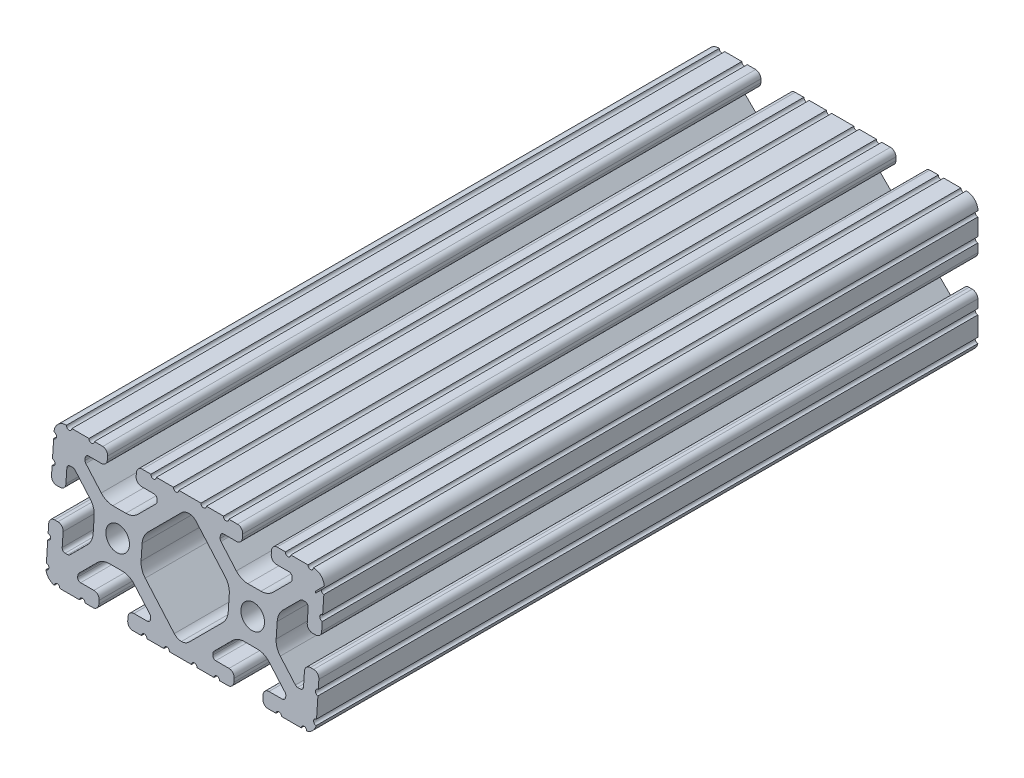
SolidWorks part; units mm, degrees
material "6005A-T61"
ref_plane "Front Plane" through (0, 0, 0) normal (0, 0, 1) x (1, 0, 0)
ref_plane "Top Plane" through (0, 0, 0) normal (0, 1, 0) x (1, 0, 0)
ref_plane "Right Plane" through (0, 0, 0) normal (1, 0, 0) x (0, 0, -1)
sketch "Sketch1" plane through (0, 0, 0) normal (0, 0, 1) x (1, 0, 0)
  line L0 (-3.1211, -19.05) -> (3.1211, -19.05)
  line L1 (-38.1, 10.287) -> (-38.1, 14.3752)
  line L2 (0, -34.5561) -> (0, 32.8014) construction
  line L3 (-38.1, 0) -> (0, 0) construction
  line L4 (-38.1, 9.5497) -> (-38.1, 10.287)
  line L5 (-19.05, 19.05) -> (-19.05, -20.2827) construction
  line L6 (0, -15.1247) -> (0, -15.1131) construction
  line L7 (9.1761, 12.9058) -> (13.8525, 8.2294)
  line L8 (8.9158, 14.097) -> (8.9158, 13.5344)
  line L9 (13.4112, 14.986) -> (9.8048, 14.986)
  line L10 (14.986, 17.4968) -> (14.986, 16.5608)
  line L11 (10.9975, 19.05) -> (13.4328, 19.05)
  line L12 (8.6331, 19.05) -> (9.4735, 19.05)
  line L13 (4.6451, 19.05) -> (8.6331, 19.05)
  line L14 (31.792, 10.0266) -> (27.1976, 5.4321)
  line L15 (33.147, 10.287) -> (32.4207, 10.287)
  line L16 (29.2071, 19.05) -> (33.2963, 19.05)
  line L17 (28.4698, 19.05) -> (29.2071, 19.05)
  line L18 (-38.1, 5.6388) -> (-38.1, 8.0257)
  line L19 (24.5589, 19.05) -> (26.9458, 19.05)
  line L20 (23.114, 16.5608) -> (23.114, 17.4806)
  line L21 (28.2952, 14.986) -> (24.6888, 14.986)
  line L22 (29.1842, 13.5344) -> (29.1842, 14.097)
  line L23 (-34.036, 9.398) -> (-34.036, 5.6388)
  line L24 (-35.6108, 4.064) -> (-36.5252, 4.064)
  line L25 (24.2475, 8.2294) -> (28.9239, 12.9058)
  line L26 (25.8064, -2.0735) -> (25.8064, 2.0735)
  line L27 (35.6108, 4.064) -> (36.5252, 4.064)
  line L28 (34.036, 9.398) -> (34.036, 5.6388)
  line L29 (38.1, 5.6388) -> (38.1, 8.0257)
  line L30 (38.1, 9.5497) -> (38.1, 10.287)
  line L31 (38.1, 10.287) -> (38.1, 14.3752)
  line L32 (17.2111, 6.8382) -> (20.8889, 6.8382)
  line L33 (2.077, 14.2576) -> (10.9024, 5.4321)
  line L34 (-31.792, -10.0266) -> (-27.1976, -5.4321)
  line L35 (-33.147, -10.287) -> (-32.4207, -10.287)
  line L36 (-29.2071, -19.05) -> (-34.0473, -19.05)
  line L37 (-28.4698, -19.05) -> (-29.2071, -19.05)
  line L38 (-24.6888, -19.05) -> (-26.9458, -19.05)
  line L39 (12.2936, -2.0735) -> (12.2936, 2.0735)
  line L40 (-23.114, -16.5608) -> (-23.114, -17.4752)
  line L41 (-28.448, -14.986) -> (-24.6888, -14.986)
  line L42 (-29.337, -13.6872) -> (-29.337, -14.097)
  line L43 (2.077, -14.2576) -> (10.9024, -5.4321)
  line L44 (-3.1211, 19.05) -> (3.1211, 19.05)
  line L45 (8.763, -14.097) -> (8.763, -13.6872)
  line L46 (-24.2475, -8.2294) -> (-29.0766, -13.0586)
  line L47 (-35.6108, -4.064) -> (-36.5252, -4.064)
  line L48 (-34.036, -9.398) -> (-34.036, -5.6388)
  line L49 (-38.1, -5.6388) -> (-38.1, -8.0257)
  line L50 (-38.1, -9.5497) -> (-38.1, -10.287)
  line L51 (-38.1, -10.287) -> (-38.1, -15.036)
  line L52 (17.2111, -6.8382) -> (20.8889, -6.8382)
  line L53 (38.1, -10.287) -> (38.1, -15.036)
  line L54 (38.1, -9.5497) -> (38.1, -10.287)
  line L55 (38.1, -5.6388) -> (38.1, -8.0257)
  line L56 (34.036, -9.398) -> (34.036, -5.6388)
  line L57 (35.6108, -4.064) -> (36.5252, -4.064)
  line L58 (24.2475, -8.2294) -> (29.0766, -13.0586)
  line L59 (29.337, -13.6872) -> (29.337, -14.097)
  line L60 (-17.2111, -6.8382) -> (-20.8889, -6.8382)
  line L61 (-9.0234, -13.0586) -> (-13.8525, -8.2294)
  line L62 (-8.763, -14.097) -> (-8.763, -13.6872)
  line L63 (-13.4112, -14.986) -> (-9.652, -14.986)
  line L64 (-14.986, -17.4752) -> (-14.986, -16.5608)
  line L65 (-10.9975, -19.05) -> (-13.4112, -19.05)
  line L66 (28.448, -14.986) -> (24.6888, -14.986)
  line L67 (23.114, -16.5608) -> (23.114, -17.4752)
  line L68 (24.6888, -19.05) -> (26.9458, -19.05)
  line L69 (28.4698, -19.05) -> (29.2071, -19.05)
  line L70 (29.2071, -19.05) -> (34.0473, -19.05)
  line L71 (-8.6331, -19.05) -> (-9.4735, -19.05)
  line L72 (33.147, -10.287) -> (32.4207, -10.287)
  line L73 (31.792, -10.0266) -> (27.1976, -5.4321)
  line L74 (-4.6451, -19.05) -> (-8.6331, -19.05)
  line L75 (9.0234, -13.0586) -> (13.8525, -8.2294)
  line L76 (13.4112, -14.986) -> (9.652, -14.986)
  line L77 (-2.077, -14.2576) -> (-10.9024, -5.4321)
  line L78 (14.986, -17.4752) -> (14.986, -16.5608)
  line L79 (10.9975, -19.05) -> (13.4112, -19.05)
  line L80 (4.6451, -19.05) -> (8.6331, -19.05)
  line L81 (8.6331, -19.05) -> (9.4735, -19.05)
  line L83 (-12.2936, -2.0735) -> (-12.2936, 2.0735)
  line L84 (-25.8064, -2.0735) -> (-25.8064, 2.0735)
  line L85 (-2.077, 14.2576) -> (-10.9024, 5.4321)
  line L87 (-4.6451, 19.05) -> (-8.6331, 19.05)
  line L88 (-8.6331, 19.05) -> (-9.4735, 19.05)
  line L89 (-10.9975, 19.05) -> (-13.4328, 19.05)
  line L90 (-14.986, 17.4968) -> (-14.986, 16.5608)
  line L91 (-13.4112, 14.986) -> (-9.8048, 14.986)
  line L92 (-8.9158, 14.097) -> (-8.9158, 13.5344)
  line L93 (-9.1761, 12.9058) -> (-13.8525, 8.2294)
  line L94 (-17.2111, 6.8382) -> (-20.8889, 6.8382)
  line L95 (-24.2475, 8.2294) -> (-28.9239, 12.9058)
  line L96 (-29.1842, 13.5344) -> (-29.1842, 14.097)
  line L97 (-28.2952, 14.986) -> (-24.6888, 14.986)
  line L98 (-23.114, 16.5608) -> (-23.114, 17.4806)
  line L99 (-24.5589, 19.05) -> (-26.9458, 19.05)
  line L100 (-28.4698, 19.05) -> (-29.2071, 19.05)
  line L101 (-29.2071, 19.05) -> (-33.2963, 19.05)
  line L109 (-33.147, 10.287) -> (-32.4207, 10.287)
  line L165 (-31.792, 10.0266) -> (-27.1976, 5.4321)
  arc A0 (-38.1376, 15.8983) -> (-38.1, 14.3752) centre (-38.1, 15.1372) cw
  arc A1 (-38.1, 9.5497) -> (-38.1, 8.0257) centre (-38.1, 8.7877) cw
  arc A2 (9.1761, 12.9058) -> (8.9158, 13.5344) centre (9.8048, 13.5344) cw
  arc A3 (8.9158, 14.097) -> (9.8048, 14.986) centre (9.8048, 14.097) cw
  arc A4 (-36.5252, 4.064) -> (-38.1, 5.6388) centre (-36.5252, 5.6388) cw
  arc A5 (14.986, 16.5608) -> (13.4112, 14.986) centre (13.4112, 16.5608) cw
  arc A6 (13.4328, 19.05) -> (14.986, 17.4968) centre (13.4328, 17.4968) cw
  arc A7 (10.9975, 19.05) -> (9.4735, 19.05) centre (10.2355, 19.05) cw
  arc A8 (4.6451, 19.05) -> (3.1211, 19.05) centre (3.8831, 19.05) cw
  arc A9 (0, 15.1131) -> (2.077, 14.2576) centre (0.0116, 12.1921) cw
  arc A10 (25.8064, 2.0735) -> (27.1976, 5.4321) centre (30.5562, 2.0735) cw
  arc A11 (31.792, 10.0266) -> (32.4207, 10.287) centre (32.4207, 9.398) cw
  arc A12 (33.147, 10.287) -> (34.036, 9.398) centre (33.147, 9.398) cw
  arc A13 (34.8195, 19.0968) -> (38.1376, 15.8983) centre (34.903, 15.8631) cw
  arc A14 (34.8195, 19.0968) -> (33.2963, 19.05) centre (34.0579, 19.0734) cw
  arc A15 (28.4698, 19.05) -> (26.9458, 19.05) centre (27.7078, 19.05) cw
  arc A16 (23.114, 17.4806) -> (24.5589, 19.05) centre (24.6888, 17.4806) cw
  arc A17 (24.6888, 14.986) -> (23.114, 16.5608) centre (24.6888, 16.5608) cw
  arc A18 (28.2952, 14.986) -> (29.1842, 14.097) centre (28.2952, 14.097) cw
  arc A19 (29.1842, 13.5344) -> (28.9239, 12.9058) centre (28.2952, 13.5344) cw
  arc A20 (-35.5713, -19.05) -> (-38.1, -16.56) centre (-34.9455, -15.8855) cw
  arc A21 (34.036, 5.6388) -> (35.6108, 4.064) centre (35.6108, 5.6388) ccw
  arc A22 (36.5252, 4.064) -> (38.1, 5.6388) centre (36.5252, 5.6388) ccw
  arc A23 (38.1, 9.5497) -> (38.1, 8.0257) centre (38.1, 8.7877) ccw
  arc A24 (24.2475, 8.2294) -> (20.8889, 6.8382) centre (20.8889, 11.588) cw
  arc A25 (17.2111, 6.8382) -> (13.8525, 8.2294) centre (17.2111, 11.588) cw
  arc A26 (10.9024, 5.4321) -> (12.2936, 2.0735) centre (7.5438, 2.0735) cw
  arc A27 (0, -15.1131) -> (2.077, -14.2576) centre (0.0116, -12.1921) ccw
  arc A28 (-34.036, 5.6388) -> (-35.6108, 4.064) centre (-35.6108, 5.6388) cw
  arc A29 (-25.8064, -2.0735) -> (-27.1976, -5.4321) centre (-30.5562, -2.0735) cw
  arc A30 (-31.792, -10.0266) -> (-32.4207, -10.287) centre (-32.4207, -9.398) cw
  arc A31 (-33.147, -10.287) -> (-34.036, -9.398) centre (-33.147, -9.398) cw
  arc A33 (-35.5713, -19.05) -> (-34.0473, -19.05) centre (-34.8093, -19.05) cw
  arc A34 (-28.4698, -19.05) -> (-26.9458, -19.05) centre (-27.7078, -19.05) cw
  arc A35 (10.9024, -5.4321) -> (12.2936, -2.0735) centre (7.5438, -2.0735) ccw
  circle A36 centre (19.05, 0) radius 3.3274
  arc A37 (-23.114, -17.4752) -> (-24.6888, -19.05) centre (-24.6888, -17.4752) cw
  arc A38 (-24.6888, -14.986) -> (-23.114, -16.5608) centre (-24.6888, -16.5608) cw
  arc A39 (-28.448, -14.986) -> (-29.337, -14.097) centre (-28.448, -14.097) cw
  arc A40 (-29.337, -13.6872) -> (-29.0766, -13.0586) centre (-28.448, -13.6872) cw
  arc A41 (-24.2475, -8.2294) -> (-20.8889, -6.8382) centre (-20.8889, -11.588) cw
  arc A42 (-34.036, -5.6388) -> (-35.6108, -4.064) centre (-35.6108, -5.6388) ccw
  arc A43 (-36.5252, -4.064) -> (-38.1, -5.6388) centre (-36.5252, -5.6388) ccw
  arc A44 (-38.1, -9.5497) -> (-38.1, -8.0257) centre (-38.1, -8.7877) ccw
  arc A45 (-38.1, -16.56) -> (-38.1, -15.036) centre (-38.1, -15.798) ccw
  arc A46 (38.1, -16.56) -> (38.1, -15.036) centre (38.1, -15.798) cw
  arc A47 (38.1, -9.5497) -> (38.1, -8.0257) centre (38.1, -8.7877) cw
  arc A48 (36.5252, -4.064) -> (38.1, -5.6388) centre (36.5252, -5.6388) cw
  arc A49 (34.036, -5.6388) -> (35.6108, -4.064) centre (35.6108, -5.6388) cw
  arc A50 (24.2475, -8.2294) -> (20.8889, -6.8382) centre (20.8889, -11.588) ccw
  arc A51 (29.337, -13.6872) -> (29.0766, -13.0586) centre (28.448, -13.6872) ccw
  arc A52 (28.448, -14.986) -> (29.337, -14.097) centre (28.448, -14.097) ccw
  arc A53 (24.6888, -14.986) -> (23.114, -16.5608) centre (24.6888, -16.5608) ccw
  arc A54 (-17.2111, -6.8382) -> (-13.8525, -8.2294) centre (-17.2111, -11.588) cw
  arc A55 (-9.0234, -13.0586) -> (-8.763, -13.6872) centre (-9.652, -13.6872) cw
  arc A56 (-8.763, -14.097) -> (-9.652, -14.986) centre (-9.652, -14.097) cw
  arc A57 (-14.986, -16.5608) -> (-13.4112, -14.986) centre (-13.4112, -16.5608) cw
  arc A58 (-13.4112, -19.05) -> (-14.986, -17.4752) centre (-13.4112, -17.4752) cw
  arc A59 (-10.9975, -19.05) -> (-9.4735, -19.05) centre (-10.2355, -19.05) cw
  arc A60 (-4.6451, -19.05) -> (-3.1211, -19.05) centre (-3.8831, -19.05) cw
  arc A61 (23.114, -17.4752) -> (24.6888, -19.05) centre (24.6888, -17.4752) ccw
  arc A62 (28.4698, -19.05) -> (26.9458, -19.05) centre (27.7078, -19.05) ccw
  arc A63 (35.5713, -19.05) -> (34.0473, -19.05) centre (34.8093, -19.05) ccw
  arc A64 (35.5713, -19.05) -> (38.1, -16.56) centre (34.9379, -15.8778) ccw
  arc A65 (33.147, -10.287) -> (34.036, -9.398) centre (33.147, -9.398) ccw
  arc A66 (31.792, -10.0266) -> (32.4207, -10.287) centre (32.4207, -9.398) ccw
  arc A67 (-10.9024, -5.4321) -> (-12.2936, -2.0735) centre (-7.5438, -2.0735) cw
  arc A68 (0, -15.1131) -> (-2.077, -14.2576) centre (-0.0116, -12.1921) cw
  arc A69 (0, 15.1131) -> (-2.077, 14.2576) centre (-0.0116, 12.1921) ccw
  arc A70 (-10.9024, 5.4321) -> (-12.2936, 2.0735) centre (-7.5438, 2.0735) ccw
  arc A71 (25.8064, -2.0735) -> (27.1976, -5.4321) centre (30.5562, -2.0735) ccw
  arc A72 (9.0234, -13.0586) -> (8.763, -13.6872) centre (9.652, -13.6872) ccw
  arc A73 (8.763, -14.097) -> (9.652, -14.986) centre (9.652, -14.097) ccw
  arc A74 (17.2111, -6.8382) -> (13.8525, -8.2294) centre (17.2111, -11.588) ccw
  arc A75 (13.4112, -19.05) -> (14.986, -17.4752) centre (13.4112, -17.4752) ccw
  arc A76 (14.986, -16.5608) -> (13.4112, -14.986) centre (13.4112, -16.5608) ccw
  arc A77 (-4.6451, 19.05) -> (-3.1211, 19.05) centre (-3.8831, 19.05) ccw
  arc A78 (-10.9975, 19.05) -> (-9.4735, 19.05) centre (-10.2355, 19.05) ccw
  arc A79 (-13.4328, 19.05) -> (-14.986, 17.4968) centre (-13.4328, 17.4968) ccw
  arc A80 (-14.986, 16.5608) -> (-13.4112, 14.986) centre (-13.4112, 16.5608) ccw
  arc A81 (-8.9158, 14.097) -> (-9.8048, 14.986) centre (-9.8048, 14.097) ccw
  arc A82 (-9.1761, 12.9058) -> (-8.9158, 13.5344) centre (-9.8048, 13.5344) ccw
  arc A83 (-17.2111, 6.8382) -> (-13.8525, 8.2294) centre (-17.2111, 11.588) ccw
  arc A84 (-24.2475, 8.2294) -> (-20.8889, 6.8382) centre (-20.8889, 11.588) ccw
  arc A85 (-29.1842, 13.5344) -> (-28.9239, 12.9058) centre (-28.2952, 13.5344) ccw
  arc A86 (-28.2952, 14.986) -> (-29.1842, 14.097) centre (-28.2952, 14.097) ccw
  arc A87 (-24.6888, 14.986) -> (-23.114, 16.5608) centre (-24.6888, 16.5608) ccw
  arc A88 (-23.114, 17.4806) -> (-24.5589, 19.05) centre (-24.6888, 17.4806) ccw
  arc A89 (-28.4698, 19.05) -> (-26.9458, 19.05) centre (-27.7078, 19.05) ccw
  arc A90 (-34.8195, 19.0968) -> (-33.2963, 19.05) centre (-34.0579, 19.0734) ccw
  arc A91 (-34.8195, 19.0968) -> (-38.1376, 15.8983) centre (-34.903, 15.8631) ccw
  arc A92 (4.6451, -19.05) -> (3.1211, -19.05) centre (3.8831, -19.05) ccw
  arc A93 (10.9975, -19.05) -> (9.4735, -19.05) centre (10.2355, -19.05) ccw
  arc A94 (38.1376, 15.8983) -> (38.1, 14.3752) centre (38.1, 15.1372) ccw
  arc A96 (-33.147, 10.287) -> (-34.036, 9.398) centre (-33.147, 9.398) ccw
  arc A97 (-31.792, 10.0266) -> (-32.4207, 10.287) centre (-32.4207, 9.398) ccw
  arc A98 (-25.8064, 2.0735) -> (-27.1976, 5.4321) centre (-30.5562, 2.0735) ccw
  circle A101 centre (-19.05, 0) radius 3.3274
  point P34 (0, 19.05)
  point P79 (25.6765, 0)
  point P274 (0, -19.05)
  point P282 (-25.6765, 0)
  point P283 (-12.2936, 0)
  dimension "D1" = 38.1
  dimension "D4" = 6.6548
  dimension "D10" = 4.064
  dimension "D2" = 76.2
  dimension "D3" = 38.1
  dimension "D5" = 8.128
  dimension "D6" = 20.574
  dimension "D7" = 12.2936
  dimension "D8" = 4.064
  dimension "D9" = 4.064
extrude "Extrude1" add sketch "Sketch1" against normal blind 186.817
sketch "Sketch2" plane through (38.1, 0, 0) normal (1, 0, 0) x (0, 0, -1)
  line L0 (0, -19.05) -> (0, 19.0979)
  line L1 (0, 19.0979) -> (2.6676, 19.0979)
  line L2 (186.817, 19.0979) -> (0, 19.0979) construction
  line L3 (2.6676, 19.0979) -> (0, -19.05)
  dimension "D1" = 4
extrude "Cut-Extrude1" cut sketch "Sketch2" against normal blind 127
